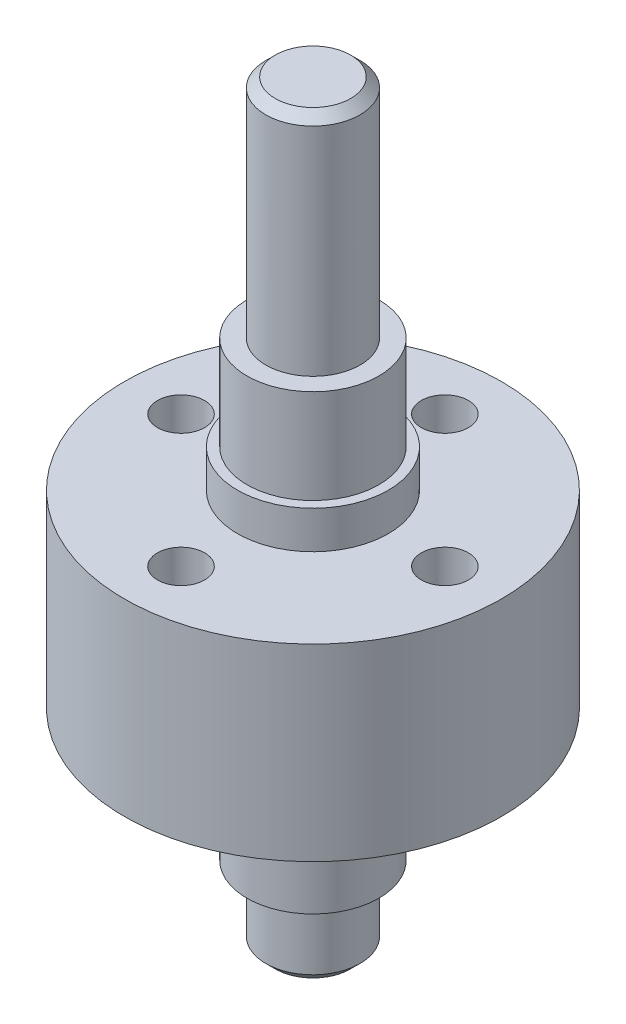
SolidWorks part; units mm, degrees
material "6061-T6 (SS)"
ref_plane "前视基准面" through (0, 0, 0) normal (0, 0, 1) x (1, 0, 0)
ref_plane "上视基准面" through (0, 0, 0) normal (0, 1, 0) x (1, 0, 0)
ref_plane "右视基准面" through (0, 0, 0) normal (1, 0, 0) x (0, 0, -1)
sketch "草图1" plane through (0, 0, 0) normal (0, 0, 1) x (1, 0, 0)
  line L0 (0, 0) -> (0, 40) construction
  line L1 (0, 0) -> (0, 40)
  line L2 (0, 40) -> (2.5, 40)
  line L3 (3.5, 28) -> (3.5, 23)
  line L4 (3.5, 23) -> (4, 23)
  line L5 (4, 23) -> (4, 21)
  line L6 (4, 21) -> (10, 21)
  line L7 (10, 21) -> (10, 11)
  line L8 (10, 11) -> (4, 11)
  line L9 (4, 11) -> (4, 9)
  line L10 (4, 9) -> (3.5, 9)
  line L11 (3.5, 9) -> (3.5, 4)
  line L12 (2.5, 0) -> (0, 0)
  line L13 (2.5, 40) -> (2.5, 28)
  line L14 (2.5, 28) -> (3.5, 28)
  line L15 (2.5, 0) -> (2.5, 4)
  line L16 (2.5, 4) -> (3.5, 4)
  dimension "D1" = 5
  dimension "D2" = 7
  dimension "D3" = 8
  dimension "D4" = 10
  dimension "D5" = 4
  dimension "D6" = 2
  dimension "D7" = 20
  dimension "D8" = 2.5
  dimension "D9" = 40
revolve "旋转1" add sketch "草图1" angle 360 about L0
hole_wizard "M3 螺纹孔1" positions "草图3" profile "草图4" tap size "M3" standard "GB" end condition through all
sketch "草图3" plane through (0, 21, 0) normal (0, 1, 0) x (1, 0, 0)
  circle A0 centre (0, 0) radius 7
  point P0 (0, 7)
  point P2 (7, 0)
  point P4 (0, -7)
  point P6 (-7, 0)
  dimension "D1" = 14
sketch "草图4" plane through (0, 21, -7) normal (1, 0, 0) x (0, 0, 1)
  line L0 (0, 0) -> (0, 21)
  line L1 (0, 21) -> (1.25, 21)
  line L2 (1.25, 21) -> (1.25, 0)
  line L5 (1.25, 0) -> (0, 0)
  line L11 (0, -6.35) -> (0, 107.95) construction
  dimension "通孔螺纹孔钻头直径" = 2.5
  dimension "通孔螺纹孔钻头深度" = 21
cosmetic thread "孔螺蚊线1" parameters "D2"=3
cosmetic thread "孔螺蚊线2" parameters "D2"=3
cosmetic thread "孔螺蚊线3" parameters "D2"=3
cosmetic thread "孔螺蚊线4" parameters "D2"=3
chamfer "倒角1" distance 0.5 angle 45 2 edges at (0, 0, -2.5) (0, 40, -2.5)
